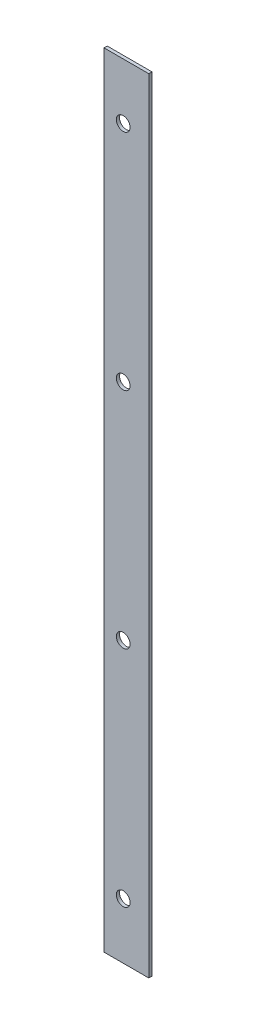
SolidWorks part; units mm, degrees
ref_plane "Спереди" through (0, 0, 0) normal (0, 0, 1) x (1, 0, 0)
ref_plane "Сверху" through (0, 0, 0) normal (0, 1, 0) x (1, 0, 0)
ref_plane "Справа" through (0, 0, 0) normal (1, 0, 0) x (0, 0, -1)
sketch "Эскиз1" plane through (0, 0, 0) normal (0, 0, 1) x (1, 0, 0)
  line L0 (0, 131.9308) -> (0, -134.9775) construction
  line L1 (0, 0) -> (52.8204, 0) construction
  line L2 (-6, -122.5) -> (8, -122.5)
  line L3 (-6, -122.5) -> (-6, 122.5)
  line L4 (-6, 122.5) -> (8, 122.5)
  line L5 (8, -122.5) -> (8, 122.5)
  circle A0 centre (0, -105) radius 2.15
  circle A1 centre (0, -35) radius 2.15
  circle A2 centre (0, 35) radius 2.15
  circle A3 centre (0, 105) radius 2.15
  dimension "D4" = 4.3
  dimension "D6" = 70
  dimension "D7" = 70
  dimension "D8" = 210
  dimension "D1" = 14
  dimension "D2" = 6
  dimension "D3" = 245
  dimension "D5" = 17.5
extrude "Вытянуть1" add sketch "Эскиз1" along normal blind 1
